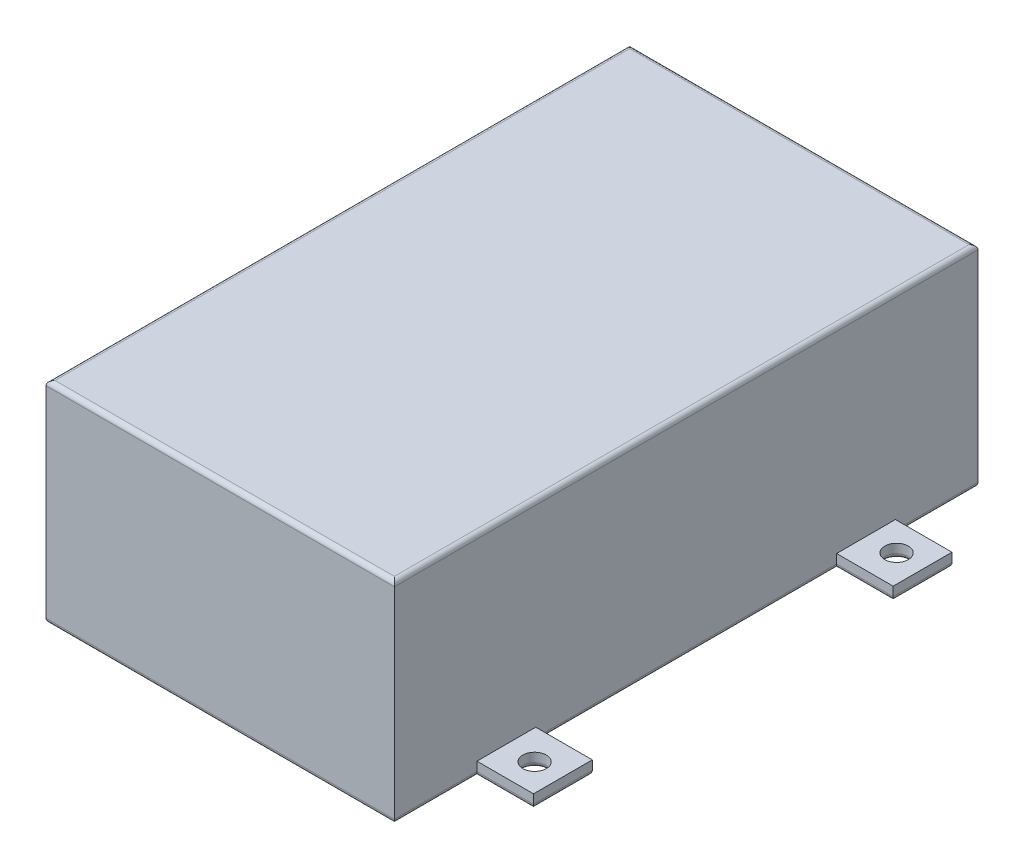
SolidWorks part; units mm, degrees
material "AISI 304"
ref_plane "前视基准面" through (0, 0, 0) normal (0, 0, 1) x (1, 0, 0)
ref_plane "上视基准面" through (0, 0, 0) normal (0, 1, 0) x (1, 0, 0)
ref_plane "右视基准面" through (0, 0, 0) normal (1, 0, 0) x (0, 0, -1)
other "Configuration Table"
sketch "草图1" plane through (0, 0, 0) normal (0, 1, 0) x (1, 0, 0)
  line L1 (-38.5, -64.5) -> (38.5, -64.5)
  line L2 (-38.5, -64.5) -> (-38.5, 64.5)
  line L3 (-38.5, 64.5) -> (38.5, 64.5)
  line L4 (38.5, -64.5) -> (38.5, 64.5)
  line L5 (-38.5, -64.5) -> (38.5, 64.5) construction
  line L6 (-38.5, 64.5) -> (38.5, -64.5) construction
  point P0 (0, 0)
  dimension "D1" = 77
  dimension "D2" = 129
extrude "凸台-拉伸1" add sketch "草图1" along normal blind 46.5
sketch "草图2" plane through (0, 0, 0) normal (0, -1, 0) x (1, 0, 0)
  line L0 (0, 0) -> (0, 64.5) construction
  line L1 (-38.5, 64.5) -> (38.5, 64.5) construction
  line L2 (0, 0) -> (64.8836, 0) construction
  line L3 (-38.5, 46.25) -> (-51, 46.25)
  line L4 (-38.5, -64.5) -> (-38.5, 64.5) construction
  line L5 (-51, 46.25) -> (-51, 33.25)
  line L6 (-51, 33.25) -> (-38.5, 33.25)
  line L7 (-38.5, 33.25) -> (-38.5, 46.25)
  line L8 (38.5, 33.25) -> (38.5, 46.25)
  line L9 (51, 33.25) -> (38.5, 33.25)
  line L10 (51, 46.25) -> (51, 33.25)
  line L11 (38.5, 46.25) -> (51, 46.25)
  line L12 (38.5, -46.25) -> (51, -46.25)
  line L13 (51, -46.25) -> (51, -33.25)
  line L14 (51, -33.25) -> (38.5, -33.25)
  line L15 (38.5, -33.25) -> (38.5, -46.25)
  line L16 (-38.5, -33.25) -> (-38.5, -46.25)
  line L17 (-51, -33.25) -> (-38.5, -33.25)
  line L18 (-51, -46.25) -> (-51, -33.25)
  line L19 (-38.5, -46.25) -> (-51, -46.25)
  circle A0 centre (-45, 40) radius 2.6
  circle A1 centre (45, 40) radius 2.6
  circle A2 centre (45, -40) radius 2.6
  circle A3 centre (-45, -40) radius 2.6
  dimension "D1" = 5.2
  dimension "D3" = 90
  dimension "D4" = 80
  dimension "D2" = 102
  dimension "D5" = 13
  dimension "D6" = 66.5
extrude "凸台-拉伸2" add sketch "草图2" against normal blind 3
sketch "草图3" plane through (0, 0, -64.5) normal (0, 0, -1) x (-1, 0, 0)
  line L0 (0, 0) -> (0, 49.4764) construction
  line L1 (-38.5, 23.25) -> (38.5, 23.25) construction
  line L2 (-38.5, 46.5) -> (-38.5, 0) construction
  line L3 (38.5, 46.5) -> (38.5, 0) construction
  circle A0 centre (25, 23.25) radius 4
  dimension "D1" = 8
  dimension "D2" = 25
extrude "切除-拉伸1" cut sketch "草图3" against normal blind 5
fillet "圆角1" radius 1 28 edges at (-45, 0, -37.4) (45, 0, -42.6) (45, 0, 42.6) (-45, 0, 37.4) (44.75, 0, 46.25) (51, 0, 39.75) (44.75, 0, 33.25) (38.5, 0, 0) (44.75, 0, -33.25) (51, 0, -39.75) (44.75, 0, -46.25) (38.5, 0, -55.375) (0, 0, -64.5) (-38.5, 0, -55.375) (-44.75, 0, -46.25) (-51, 0, -39.75) (-44.75, 0, -33.25) (-38.5, 0, 0) (-44.75, 0, 33.25) (-51, 0, 39.75) (-44.75, 0, 46.25) (-38.5, 0, 55.375) (0, 0, 64.5) (38.5, 0, 55.375) (0, 46.5, 64.5) (-38.5, 46.5, 0) (0, 46.5, -64.5) (38.5, 46.5, 0)
